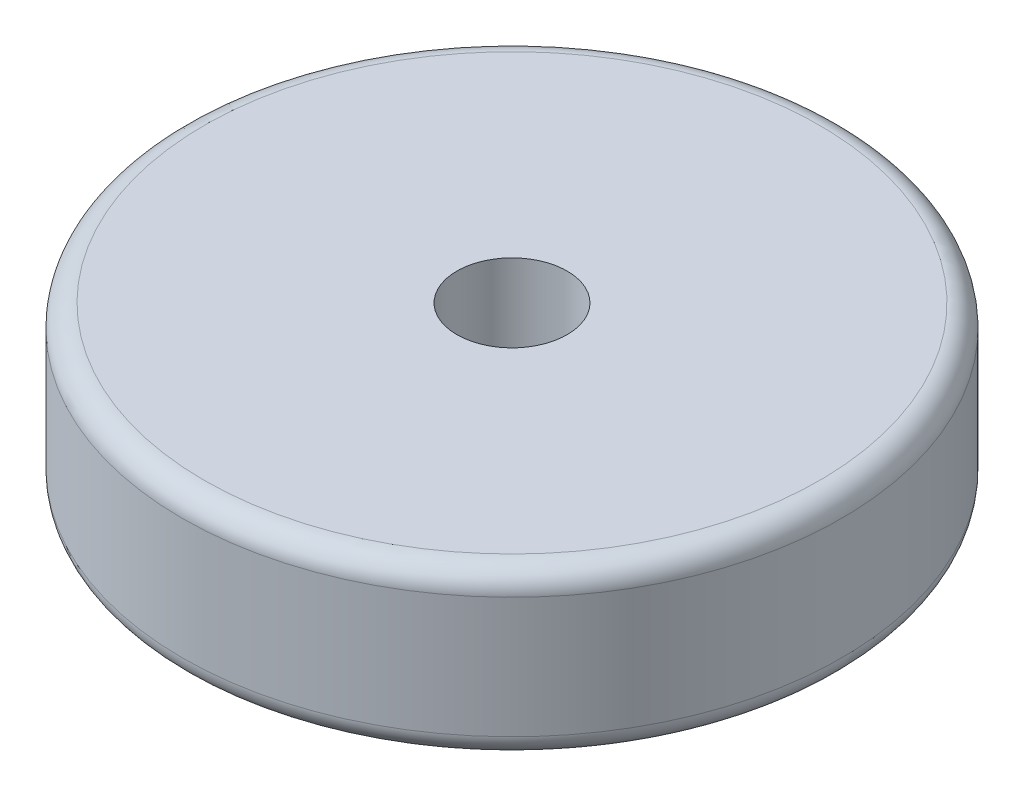
SolidWorks part; units mm, degrees
material "Rubber"
ref_plane "Front Plane" through (0, 0, 0) normal (0, 0, 1) x (1, 0, 0)
ref_plane "Top Plane" through (0, 0, 0) normal (0, 1, 0) x (1, 0, 0)
ref_plane "Right Plane" through (0, 0, 0) normal (1, 0, 0) x (0, 0, -1)
sketch "Sketch1" plane through (0, 0, 0) normal (0, 1, 0) x (1, 0, 0)
  circle A0 centre (0, 0) radius 76.2353
extrude "Boss-Extrude1" add sketch "Sketch1" along normal blind 38.1
sketch "Sketch2" plane through (0, 38.1, 0) normal (0, 1, 0) x (1, 0, 0)
  circle A0 centre (0, 0) radius 12.7579
extrude "Cut-Extrude1" cut sketch "Sketch2" against normal blind 38.1
fillet "Fillet1" radius 5.08 2 edges at (0, 0, 76.2353) (0, 38.1, 76.2353)
